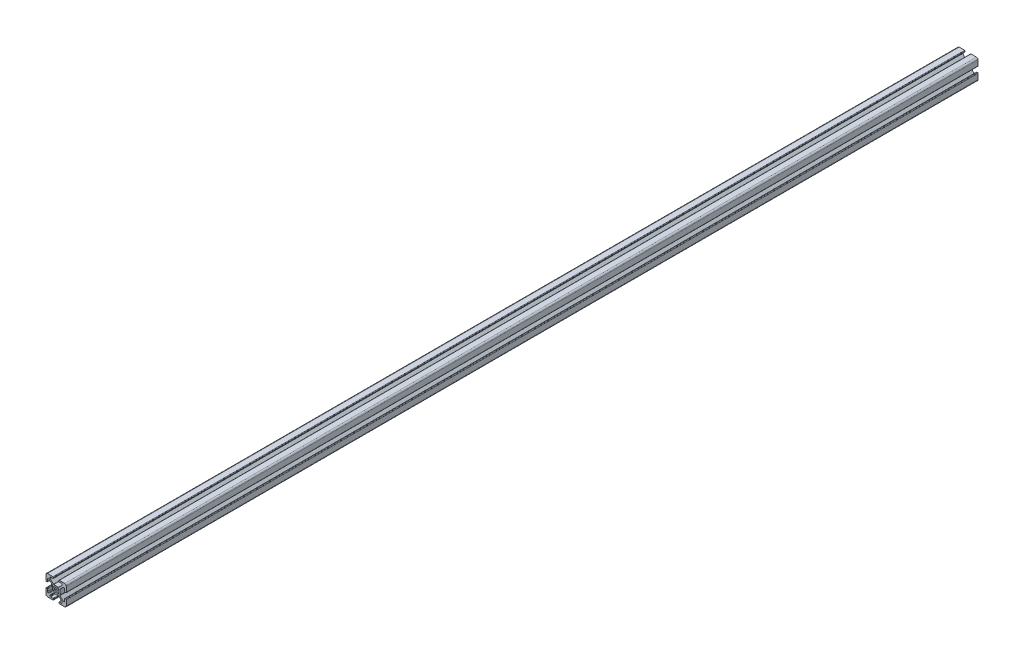
SolidWorks part; units mm, degrees
material "1060 Alloy"
ref_plane "Front Plane" through (0, 0, 0) normal (0, 0, 1) x (1, 0, 0)
ref_plane "Top Plane" through (0, 0, 0) normal (0, 1, 0) x (1, 0, 0)
ref_plane "Right Plane" through (0, 0, 0) normal (1, 0, 0) x (0, 0, -1)
sketch "Sketch2" plane through (0, 0, 0) normal (0, 0, 1) x (1, 0, 0)
  line L0 (-10, -3.138) -> (-10, -8.5)
  line L1 (-8.5, -10) -> (-3.138, -10)
  line L2 (-2.63, -9.492) -> (-2.63, -9.008)
  line L3 (-3.138, -8.5) -> (-5.487, -8.5)
  line L4 (-5.995, -7.992) -> (-5.995, -7.2662)
  line L5 (-5.8462, -6.907) -> (-2.743, -3.8038)
  line L6 (-2.3838, -3.655) -> (2.3841, -3.655)
  line L7 (2.7433, -3.8038) -> (5.8462, -6.9067)
  line L8 (5.995, -7.2659) -> (5.995, -7.992)
  line L9 (5.487, -8.5) -> (3.138, -8.5)
  line L10 (2.63, -9.008) -> (2.63, -9.492)
  line L11 (3.138, -10) -> (8.5, -10)
  line L12 (10, -8.5) -> (10, -3.138)
  line L13 (9.492, -2.63) -> (9.008, -2.63)
  line L14 (8.5, -3.138) -> (8.5, -5.487)
  line L15 (7.992, -5.995) -> (7.2662, -5.995)
  line L16 (6.907, -5.8462) -> (3.8038, -2.743)
  line L17 (3.655, -2.3838) -> (3.655, 2.3841)
  line L18 (3.8038, 2.7433) -> (6.9067, 5.8462)
  line L19 (7.2659, 5.995) -> (7.992, 5.995)
  line L20 (8.5, 5.487) -> (8.5, 3.138)
  line L21 (9.008, 2.63) -> (9.492, 2.63)
  line L22 (10, 3.138) -> (10, 8.5)
  line L23 (8.5, 10) -> (3.138, 10)
  line L24 (2.63, 9.492) -> (2.63, 9.008)
  line L25 (3.138, 8.5) -> (5.487, 8.5)
  line L26 (5.995, 7.992) -> (5.995, 7.2662)
  line L27 (5.8462, 6.907) -> (2.743, 3.8038)
  line L28 (2.3838, 3.655) -> (-2.3841, 3.655)
  line L29 (-2.7433, 3.8038) -> (-5.8462, 6.9067)
  line L30 (-5.995, 7.2659) -> (-5.995, 7.992)
  line L31 (-5.487, 8.5) -> (-3.138, 8.5)
  line L32 (-2.63, 9.008) -> (-2.63, 9.492)
  line L33 (-3.138, 10) -> (-8.5, 10)
  line L34 (-10, 8.5) -> (-10, 3.138)
  line L35 (-9.492, 2.63) -> (-9.008, 2.63)
  line L36 (-8.5, 3.138) -> (-8.5, 5.487)
  line L37 (-7.992, 5.995) -> (-7.2662, 5.995)
  line L38 (-6.907, 5.8462) -> (-3.8038, 2.743)
  line L39 (-3.655, 2.3838) -> (-3.655, -2.3841)
  line L40 (-3.8038, -2.7433) -> (-6.9067, -5.8462)
  line L41 (-7.2659, -5.995) -> (-7.992, -5.995)
  line L42 (-8.5, -5.487) -> (-8.5, -3.138)
  line L43 (-9.008, -2.63) -> (-9.492, -2.63)
  line L44 (-2.1245, 2.3045) -> (-2.3045, 2.1245)
  line L45 (2.3045, 2.1245) -> (2.1245, 2.3045)
  line L46 (2.1245, -2.3045) -> (2.3045, -2.1245)
  line L47 (-2.3045, -2.1245) -> (-2.1245, -2.3045)
  arc A0 (-10, -8.5) -> (-8.5, -10) centre (-8.5, -8.5) ccw
  arc A1 (-3.138, -10) -> (-2.63, -9.492) centre (-3.138, -9.492) ccw
  arc A2 (-2.63, -9.008) -> (-3.138, -8.5) centre (-3.138, -9.008) ccw
  arc A3 (-5.995, -7.992) -> (-5.487, -8.5) centre (-5.487, -7.992) ccw
  arc A4 (-5.8462, -6.907) -> (-5.995, -7.2662) centre (-5.487, -7.2662) ccw
  arc A5 (-2.3838, -3.655) -> (-2.743, -3.8038) centre (-2.3838, -4.163) ccw
  arc A6 (2.7433, -3.8038) -> (2.3841, -3.655) centre (2.3841, -4.163) ccw
  arc A7 (5.995, -7.2659) -> (5.8462, -6.9067) centre (5.487, -7.2659) ccw
  arc A8 (5.487, -8.5) -> (5.995, -7.992) centre (5.487, -7.992) ccw
  arc A9 (3.138, -8.5) -> (2.63, -9.008) centre (3.138, -9.008) ccw
  arc A10 (2.63, -9.492) -> (3.138, -10) centre (3.138, -9.492) ccw
  arc A11 (8.5, -10) -> (10, -8.5) centre (8.5, -8.5) ccw
  arc A12 (10, -3.138) -> (9.492, -2.63) centre (9.492, -3.138) ccw
  arc A13 (9.008, -2.63) -> (8.5, -3.138) centre (9.008, -3.138) ccw
  arc A14 (7.992, -5.995) -> (8.5, -5.487) centre (7.992, -5.487) ccw
  arc A15 (6.907, -5.8462) -> (7.2662, -5.995) centre (7.2662, -5.487) ccw
  arc A16 (3.655, -2.3838) -> (3.8038, -2.743) centre (4.163, -2.3838) ccw
  arc A17 (3.8038, 2.7433) -> (3.655, 2.3841) centre (4.163, 2.3841) ccw
  arc A18 (7.2659, 5.995) -> (6.9067, 5.8462) centre (7.2659, 5.487) ccw
  arc A19 (8.5, 5.487) -> (7.992, 5.995) centre (7.992, 5.487) ccw
  arc A20 (8.5, 3.138) -> (9.008, 2.63) centre (9.008, 3.138) ccw
  arc A21 (9.492, 2.63) -> (10, 3.138) centre (9.492, 3.138) ccw
  arc A22 (10, 8.5) -> (8.5, 10) centre (8.5, 8.5) ccw
  arc A23 (3.138, 10) -> (2.63, 9.492) centre (3.138, 9.492) ccw
  arc A24 (2.63, 9.008) -> (3.138, 8.5) centre (3.138, 9.008) ccw
  arc A25 (5.995, 7.992) -> (5.487, 8.5) centre (5.487, 7.992) ccw
  arc A26 (5.8462, 6.907) -> (5.995, 7.2662) centre (5.487, 7.2662) ccw
  arc A27 (2.3838, 3.655) -> (2.743, 3.8038) centre (2.3838, 4.163) ccw
  arc A28 (-2.7433, 3.8038) -> (-2.3841, 3.655) centre (-2.3841, 4.163) ccw
  arc A29 (-5.995, 7.2659) -> (-5.8462, 6.9067) centre (-5.487, 7.2659) ccw
  arc A30 (-5.487, 8.5) -> (-5.995, 7.992) centre (-5.487, 7.992) ccw
  arc A31 (-3.138, 8.5) -> (-2.63, 9.008) centre (-3.138, 9.008) ccw
  arc A32 (-2.63, 9.492) -> (-3.138, 10) centre (-3.138, 9.492) ccw
  arc A33 (-8.5, 10) -> (-10, 8.5) centre (-8.5, 8.5) ccw
  arc A34 (-10, 3.138) -> (-9.492, 2.63) centre (-9.492, 3.138) ccw
  arc A35 (-9.008, 2.63) -> (-8.5, 3.138) centre (-9.008, 3.138) ccw
  arc A36 (-7.992, 5.995) -> (-8.5, 5.487) centre (-7.992, 5.487) ccw
  arc A37 (-6.907, 5.8462) -> (-7.2662, 5.995) centre (-7.2662, 5.487) ccw
  arc A38 (-3.655, 2.3838) -> (-3.8038, 2.743) centre (-4.163, 2.3838) ccw
  arc A39 (-3.8038, -2.7433) -> (-3.655, -2.3841) centre (-4.163, -2.3841) ccw
  arc A40 (-7.2659, -5.995) -> (-6.9067, -5.8462) centre (-7.2659, -5.487) ccw
  arc A41 (-8.5, -5.487) -> (-7.992, -5.995) centre (-7.992, -5.487) ccw
  arc A42 (-8.5, -3.138) -> (-9.008, -2.63) centre (-9.008, -3.138) ccw
  arc A43 (-9.492, -2.63) -> (-10, -3.138) centre (-9.492, -3.138) ccw
  arc A44 (-1.9358, 0.8037) -> (-1.9358, -0.8037) centre (0, 0) ccw
  arc A45 (-2.3045, 2.1245) -> (-1.9358, 0.8037) centre (-1.748, 1.568) ccw
  arc A46 (-0.8037, 1.9358) -> (-2.1245, 2.3045) centre (-1.568, 1.748) ccw
  arc A47 (0.8037, 1.9358) -> (-0.8037, 1.9358) centre (0, 0) ccw
  arc A48 (2.1245, 2.3045) -> (0.8037, 1.9358) centre (1.568, 1.748) ccw
  arc A49 (1.9358, 0.8037) -> (2.3045, 2.1245) centre (1.748, 1.568) ccw
  arc A50 (1.9358, -0.8037) -> (1.9358, 0.8037) centre (0, 0) ccw
  arc A51 (2.3045, -2.1245) -> (1.9358, -0.8037) centre (1.748, -1.568) ccw
  arc A52 (0.8037, -1.9358) -> (2.1245, -2.3045) centre (1.568, -1.748) ccw
  arc A53 (-0.8037, -1.9358) -> (0.8037, -1.9358) centre (0, 0) ccw
  arc A54 (-2.1245, -2.3045) -> (-0.8037, -1.9358) centre (-1.568, -1.748) ccw
  arc A55 (-1.9358, -0.8037) -> (-2.3045, -2.1245) centre (-1.748, -1.568) ccw
extrude "Boss-Extrude1" add sketch "Sketch2" against normal blind 900
